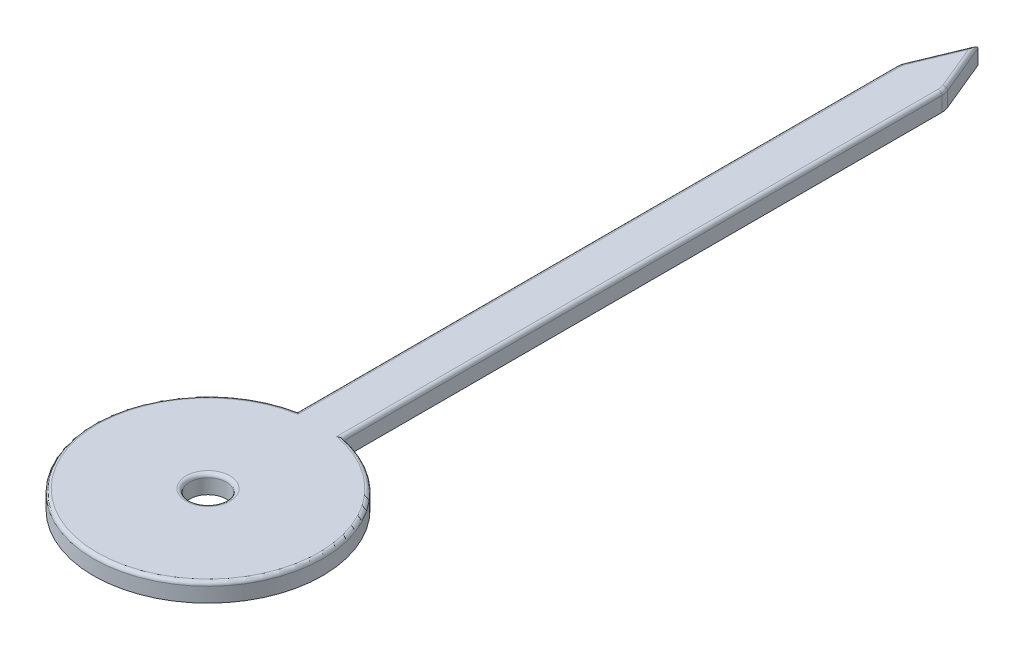
SolidWorks part; units mm, degrees
ref_plane "前视基准面" through (0, 0, 0) normal (0, 0, 1) x (1, 0, 0)
ref_plane "上视基准面" through (0, 0, 0) normal (0, 1, 0) x (1, 0, 0)
ref_plane "右视基准面" through (0, 0, 0) normal (1, 0, 0) x (0, 0, -1)
sketch "草图1" plane through (0, 0, 0) normal (0, 1, 0) x (1, 0, 0)
  line L0 (0, 0) -> (0, 4.2) construction
  line L1 (-0.125, 3.8982) -> (0, 4.2)
  line L2 (-0.125, 0.6124) -> (-0.125, 3.8982)
  line L3 (0.125, 3.8982) -> (0, 4.2)
  line L4 (0.125, 0.6124) -> (0.125, 3.8982)
  arc A0 (-0.125, 0.6124) -> (0.125, 0.6124) centre (0, 0) ccw
  circle A1 centre (0, 0) radius 0.1
  dimension "D1" = 1.25
  dimension "D5" = 0.2
  dimension "D2" = 4.2
  dimension "D3" = 0.125
  dimension "D4" = 45
extrude "凸台-拉伸1" add sketch "草图1" along normal blind 0.1
fillet "圆角1" radius 0.1 2 edges at (-0.125, 0.05, -3.8982) (0.125, 0.05, -3.8982)
fillet "圆角2" radius 0.02 8 edges at (0, 0.1, 0.1) (0.0587, 0.1, -4.0583) (0.1231, 0.1, -3.8978) (0.125, 0.1, -2.2454) (0, 0.1, 0.625) (-0.125, 0.1, -2.2454) (-0.1231, 0.1, -3.8978) (-0.0587, 0.1, -4.0583)
